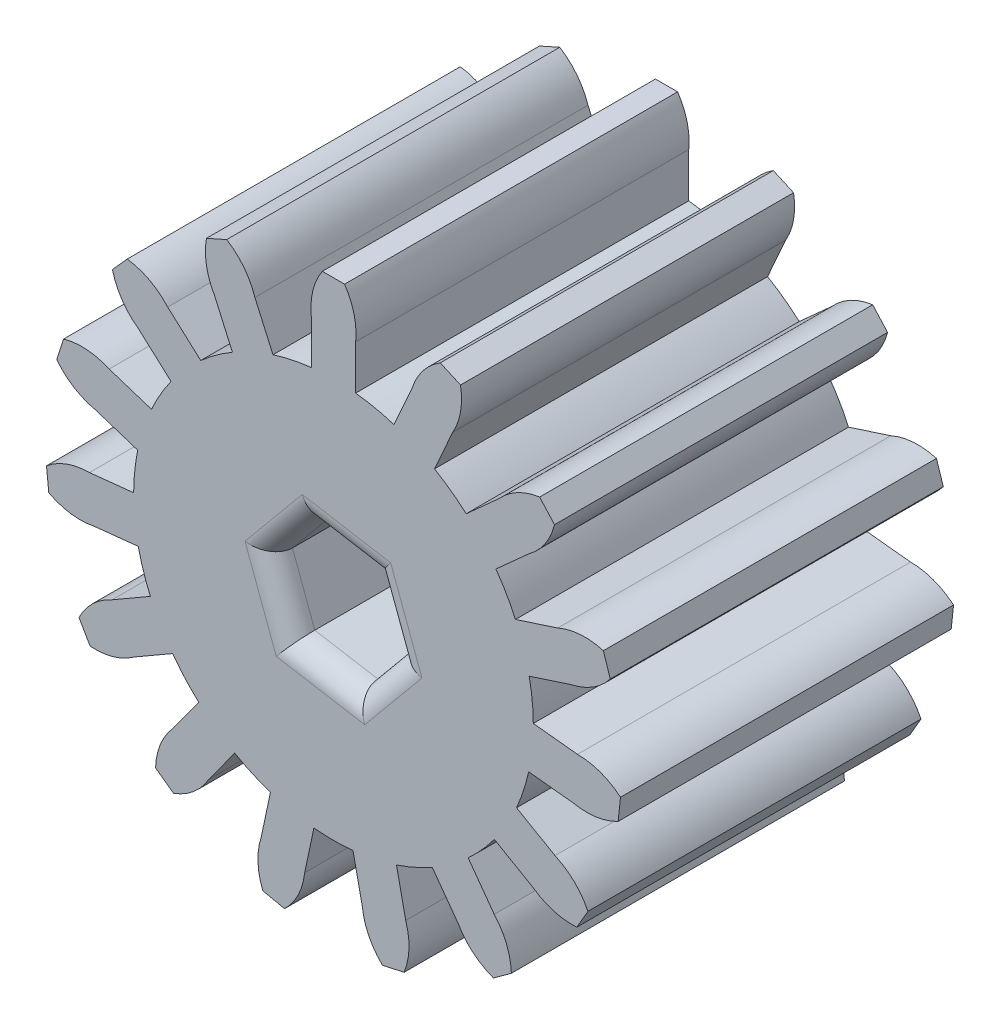
SolidWorks part; units mm, degrees
other "Markup1"
sketch "Sketch16" plane through (-12.9256, -12.7654, 5) normal (-0.0162, -0.0045, -0.9999) x (-0.9979, -0.0628, 0.0165)
ref_plane "Front Plane" through (0, 0, 0) normal (0, 0, 1) x (1, 0, 0)
ref_plane "Top Plane" through (0, 0, 0) normal (0, 1, 0) x (1, 0, 0)
ref_plane "Right Plane" through (0, 0, 0) normal (1, 0, 0) x (0, 0, -1)
sketch "Sketch1" plane through (0, 0, 0) normal (0, 0, 1) x (1, 0, 0)
  circle A0 centre (0, 0) radius 9
  circle A1 centre (0, 0) radius 1
  dimension "D1" = 2
  dimension "D2" = 18
extrude "Boss-Extrude1" add sketch "Sketch1" along normal blind 36
sketch "Sketch5" plane through (0, 0, 0) normal (1, 0, 0) x (0, 0, -1)
  line L0 (0, 0) -> (-30, 0) construction
  line L1 (-36, 9) -> (-36, -9) construction
  line L2 (-30, 0) -> (-15, 0) construction
  line L4 (-5, 4.915) -> (-5, 9)
  line L5 (0, 9) -> (-36, 9) construction
  line L6 (-36, 4.915) -> (-28, 4.915)
  line L7 (-36, 4.915) -> (-36, 9)
  line L8 (-36, 9) -> (-28, 9)
  line L9 (-28, 4.915) -> (-28, 9)
  line L10 (0, 9) -> (-5, 9)
  line L11 (0, 4.915) -> (0, 9)
  line L12 (0, 4.915) -> (-5, 4.915)
  dimension "D1" = 5
  dimension "D2" = 8
revolve "Cut-Revolve1" cut sketch "Sketch5" angle 360 about L0
sketch "Sketch6" plane through (0, 0, 0) normal (0, 0, 1) x (1, 0, 0)
  line L0 (0, 0) -> (0, 9) construction
  line L1 (-1, 8.9443) -> (-1, 10.9443)
  line L2 (-1, 8.9443) -> (1, 8.9443)
  line L3 (1, 10.9443) -> (1, 8.9443)
  line L7 (-0.5, 12.9443) -> (0.5, 12.9443)
  circle A0 centre (0, 0) radius 9 construction
  arc A1 (-1, 10.9443) -> (-0.5, 12.9443) centre (1.9832, 11.261) cw
  arc A2 (1, 10.9443) -> (0.5, 12.9443) centre (-1.9832, 11.261) ccw
  dimension "D7" = 3
  dimension "D8" = 3
  dimension "D2" = 1
  dimension "D3" = 2
  dimension "D6" = 2
extrude "Boss-Extrude2" add sketch "Sketch6" along normal blind 22
sketch "Sketch7" plane through (0, 0, 0) normal (1, 0, 0) x (0, 0, -1)
  line L0 (0, 0) -> (-5, -0.0279) construction
  line L1 (-5, -9) -> (-5, 8.9443) construction
  line L2 (-5, -0.0279) -> (-5, 15.9143) construction
  line L3 (0, 8.9443) -> (0, 10.9443) construction
  line L4 (-5, 8.9443) -> (0, 8.9443)
  line L5 (-5, 8.9443) -> (-5, 13.5982)
  line L6 (-5, 13.5982) -> (0, 13.5982)
  line L7 (0, 8.9443) -> (0, 13.5982)
  line L8 (-5, 8.9443) -> (0, 8.9443) construction
  dimension "D1" = 5
revolve "Cut-Revolve2" cut sketch "Sketch7" angle 90 about L4 other way angle 90
pattern_circular "CirPattern1" count 15 over 360 about axis through (0, 0, 0) along (0, 0, 1) of "Boss-Extrude2"
sketch "Sketch13" plane through (0, 0, 0) normal (1, 0, 0) x (0, 0, -1)
  line L0 (-25.5784, 0) -> (2.5167, 0) construction
  line L1 (-5, 16.6164) -> (0, 16.6164)
  line L2 (-5, 16.6164) -> (-5, 0)
  line L3 (-5, 0) -> (0, 0)
  line L4 (0, 16.6164) -> (0, 0)
  dimension "D1" = 5
revolve "Cut-Revolve6" cut sketch "Sketch13" angle 360 about L0
sketch "Sketch14" plane through (0, 0, 5) normal (0, 0, -1) x (-1, 0, 0)
  circle A0 centre (0, 0) radius 10.0936
ref_plane "Plane1" through (0, 0, 13.5) normal (0, 0, -1) x (-1, 0, 0)
sketch "Sketch15" plane through (0, 0, 13.5) normal (0, 0, -1) x (-1, 0, 0)
  circle A0 centre (0, 0) radius 9.3981
sketch "Sketch17" plane through (0, 0, 0) normal (0, 1, 0) x (1, 0, 0)
  circle A0 centre (-0.1287, -25.1112) radius 2
  dimension "D1" = 4
extrude "Cut-Extrude1" cut sketch "Sketch17" against normal blind 10
sketch "Sketch20" plane through (0, 0, 28) normal (0, 0, 1) x (1, 0, 0)
  circle A0 centre (0, 0) radius 20.1578
extrude "Cut-Extrude2" cut sketch "Sketch20" against normal blind 8 and the other way blind 23
sketch "Sketch21" plane through (0, 0, 20) normal (0, 0, 1) x (1, 0, 0)
  line L1 (1.841, 2.2236) -> (-1.0052, 2.7061)
  line L2 (-1.0052, 2.7061) -> (-2.8461, 0.4825)
  line L3 (-2.8461, 0.4825) -> (-1.841, -2.2236)
  line L4 (-1.841, -2.2236) -> (1.0052, -2.7061)
  line L5 (1.0052, -2.7061) -> (2.8461, -0.4825)
  line L6 (2.8461, -0.4825) -> (1.841, 2.2236)
  circle A0 centre (0, 0) radius 2.5 construction
  point P1 (1.9257, -1.5943)
  dimension "D1" = 5
extrude "Cut-Extrude3" cut sketch "Sketch21" against normal blind 36
fillet "Fillet1" radius 1 12 edges at (1.9257, -1.5943, 20) (-0.4179, -2.4648, 20) (2.3435, 0.8705, 20) (0.4179, 2.4648, 20) (-1.9257, 1.5943, 20) (-2.3435, -0.8705, 20) (1.9257, -1.5943, 5) (-0.4179, -2.4648, 5) (-2.3435, -0.8705, 5) (2.3435, 0.8705, 5) (0.4179, 2.4648, 5) (-1.9257, 1.5943, 5)
